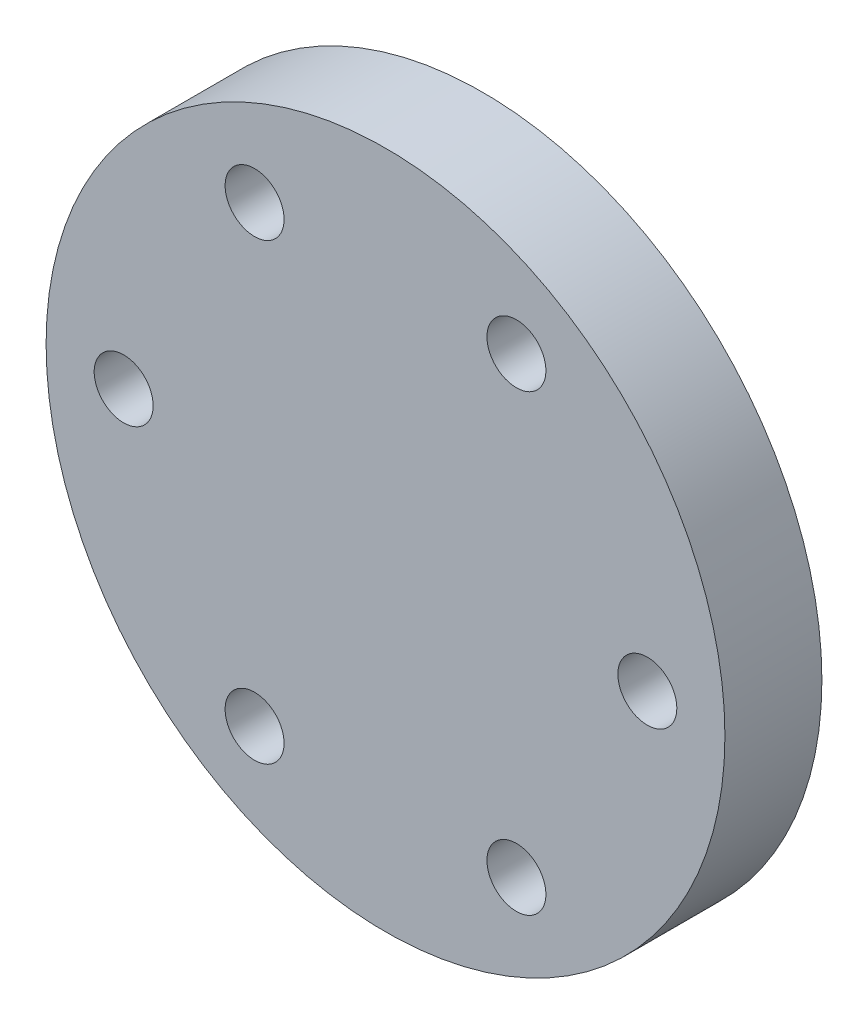
SolidWorks part; units mm, degrees
ref_plane "前视基准面" through (0, 0, 0) normal (0, 0, 1) x (1, 0, 0)
ref_plane "上视基准面" through (0, 0, 0) normal (0, 1, 0) x (1, 0, 0)
ref_plane "右视基准面" through (0, 0, 0) normal (1, 0, 0) x (0, 0, -1)
other "Configuration Table"
sketch "Profile_1" plane through (0, 0, 0) normal (0, 0, 1) x (1, 0, 0)
  circle A0 centre (0, 0) radius 17.5
  circle A1 centre (13.5, 0) radius 1.52
  circle A2 centre (6.75, 11.6913) radius 1.52
  circle A3 centre (-6.75, 11.6913) radius 1.52
  circle A4 centre (-13.5, 0) radius 1.52
  circle A5 centre (-6.75, -11.6913) radius 1.52
  circle A6 centre (6.75, -11.6913) radius 1.52
extrude "Rotating_output_interface" add sketch "Profile_1" along normal blind 5 from offset 5
